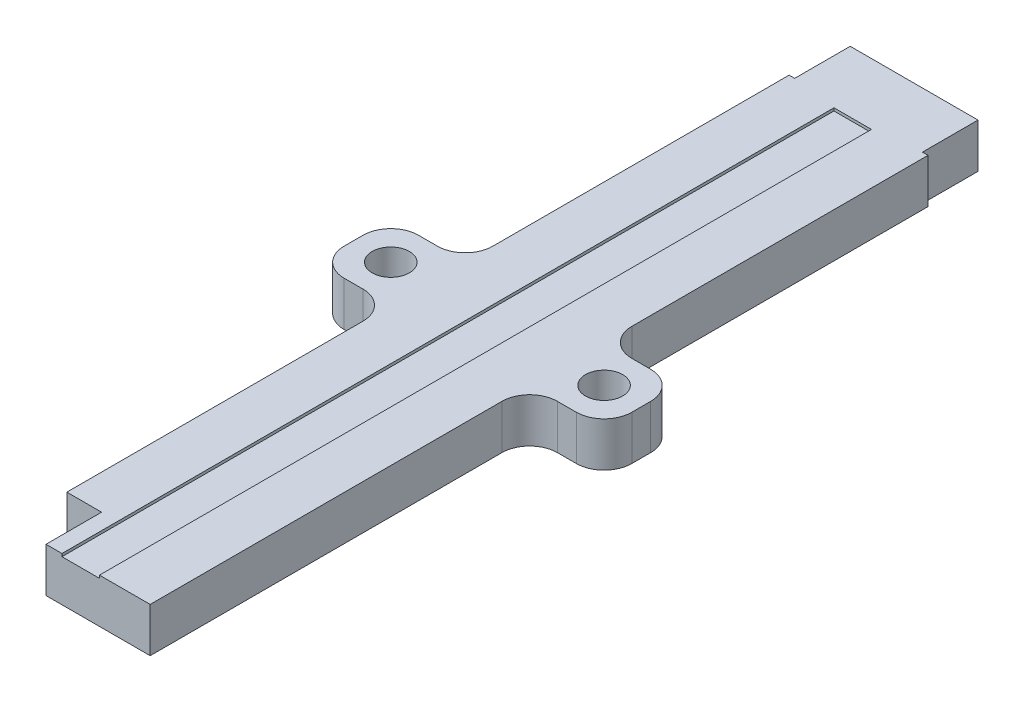
SolidWorks part; units mm, degrees
ref_plane "Front Plane" through (0, 0, 0) normal (0, 0, 1) x (1, 0, 0)
ref_plane "Top Plane" through (0, 0, 0) normal (0, 1, 0) x (1, 0, 0)
ref_plane "Right Plane" through (0, 0, 0) normal (1, 0, 0) x (0, 0, -1)
sketch "Sketch1" plane through (0, 0, 0) normal (0, 0, 1) x (1, 0, 0)
  line L1 (-6.35, -2.032) -> (6.35, -2.032)
  line L2 (-6.35, -2.032) -> (-6.35, 2.032)
  line L3 (-6.35, 2.032) -> (6.35, 2.032)
  line L4 (6.35, -2.032) -> (6.35, 2.032)
  line L5 (-6.35, -2.032) -> (6.35, 2.032) construction
  line L6 (-6.35, 2.032) -> (6.35, -2.032) construction
  point P0 (0, 0)
  dimension "D1" = 4.064
  dimension "D2" = 12.7
extrude "Boss-Extrude1" add sketch "Sketch1" along normal blind 228.6
sketch "Sketch2" plane through (0, 2.032, 0) normal (0, 1, 0) x (1, 0, 0)
  line L0 (1.7145, -114.3) -> (6.35, -114.3) construction
  line L1 (-1.7145, -5.6134) -> (1.7145, -5.6134)
  line L2 (-1.7145, -5.6134) -> (-1.7145, -222.9866)
  line L3 (-1.7145, -222.9866) -> (1.7145, -222.9866)
  line L4 (1.7145, -5.6134) -> (1.7145, -222.9866)
  line L5 (6.35, -228.6) -> (6.35, 0) construction
  line L6 (-1.7145, -114.3) -> (-6.35, -114.3) construction
  line L7 (-6.35, -228.6) -> (-6.35, 0) construction
  dimension "D1" = 3.429
  dimension "D2" = 217.3732
extrude "Cut-Extrude1" cut sketch "Sketch2" against normal blind 0.254
sketch "Sketch3" plane through (0, 2.032, 0) normal (0, 1, 0) x (1, 0, 0)
  line L1 (-6.35, -228.6) -> (-5.842, -228.6)
  line L2 (-6.35, -228.6) -> (-6.35, -223.52)
  line L3 (-6.35, -223.52) -> (-5.842, -223.52)
  line L4 (-5.842, -228.6) -> (-5.842, -223.52)
  dimension "D1" = 0.508
  dimension "D2" = 5.08
extrude "Cut-Extrude2" cut sketch "Sketch3" against normal through all
ref_plane "Plane1" through (0, 0, 114.3) normal (0, 0, -1) x (-1, 0, 0)
mirror "Mirror1" about plane through (0, 0, 114.3) normal (0, 0, -1) of "Cut-Extrude2"
mirror "Mirror2" about plane through (0, 0, 0) normal (1, 0, 0) of "Mirror1", "Cut-Extrude2"
sketch "Sketch4" plane through (0, 2.032, 0) normal (0, 1, 0) x (1, 0, 0)
  line L2 (-5.842, -228.6) -> (-2.667, -228.6)
  line L3 (-5.842, -228.6) -> (-5.842, -225.425)
  line L4 (-5.842, -225.425) -> (-2.667, -225.425)
  line L5 (-2.667, -228.6) -> (-2.667, -225.425)
  dimension "D1" = 3.175
  dimension "D2" = 3.175
extrude "Cut-Extrude3" cut sketch "Sketch4" against normal through all
sketch "Sketch5" plane through (0, 2.032, 0) normal (0, 1, 0) x (1, 0, 0)
  line L0 (5.842, 0) -> (-5.842, 0) construction
  line L1 (-6.35, 0) -> (6.35, 0) construction
  line L2 (-6.35, -71.12) -> (-6.35, -152.4)
  line L3 (-6.35, -152.4) -> (6.35, -152.4) construction
  line L4 (6.35, -76.2) -> (6.35, -152.4)
  line L5 (5.842, -228.6) -> (-2.667, -228.6) construction
  line L7 (6.35, -223.52) -> (6.35, -5.08) construction
  line L8 (-6.35, -152.4) -> (3.175, -152.4) construction
  line L9 (3.175, -152.4) -> (3.175, -155.575) construction
  line L10 (3.175, -155.575) -> (6.35, -155.575) construction
  line L11 (6.35, -155.575) -> (6.35, -152.4)
  line L12 (-6.35, -152.4) -> (-6.35, -228.6)
  line L13 (-6.35, -228.6) -> (6.35, -228.6)
  line L14 (6.35, -228.6) -> (6.35, -155.575)
  line L15 (-6.35, 0) -> (-6.35, -71.12) construction
  line L16 (-3.175, -71.12) -> (-3.175, -76.2)
  line L17 (-3.175, -76.2) -> (6.35, -76.2)
  line L18 (6.35, -76.2) -> (6.35, 0) construction
  line L19 (-6.35, -71.12) -> (-3.175, -71.12)
  dimension "D1" = 0
  dimension "D2" = 76.2
  dimension "D5" = 3.175
  dimension "D6" = 3.175
  dimension "D7" = 5.08
  dimension "D8" = 3.175
  dimension "D9" = 76.2
extrude "Cut-Extrude5" cut sketch "Sketch5" against normal through all
sketch "Sketch6" plane through (0, 2.032, 0) normal (0, 1, 0) x (1, 0, 0)
  line L0 (6.35, -76.2) -> (6.35, -5.08) construction
  line L1 (6.35, -34.6989) -> (13.1521, -34.6989)
  line L2 (6.35, -34.6989) -> (6.35, -41.5011)
  line L3 (6.35, -41.5011) -> (13.1521, -41.5011)
  line L4 (13.1521, -34.6989) -> (13.1521, -41.5011)
  line L5 (0, -5.6134) -> (0, -76.2) construction
  line L6 (1.7145, -5.6134) -> (-1.7145, -5.6134) construction
  line L7 (1.7145, -76.2) -> (-1.7145, -76.2) construction
  line L8 (9.7511, -38.1) -> (13.1521, -38.1) construction
  line L9 (5.842, 0) -> (-5.842, 0) construction
  line L10 (-9.7511, -38.1) -> (-13.1521, -38.1) construction
  line L11 (-13.1521, -34.6989) -> (-13.1521, -41.5011)
  line L12 (-6.35, -41.5011) -> (-13.1521, -41.5011)
  line L13 (-6.35, -34.6989) -> (-6.35, -41.5011)
  line L14 (-6.35, -34.6989) -> (-13.1521, -34.6989)
  circle A0 centre (9.7511, -38.1) radius 1.7005
  circle A1 centre (-9.7511, -38.1) radius 1.7005
  dimension "D1" = 3.4011
  dimension "D2" = 6.8021
  dimension "D3" = 3.4011
  dimension "D4" = 38.1
extrude "Boss-Extrude2" add sketch "Sketch6" against normal through all
fillet "Fillet1" radius 2.54 8 edges at (13.1521, 0, 41.5011) (13.1521, 0, 34.6989) (-13.1521, 0, 34.6989) (-13.1521, 0, 41.5011)
